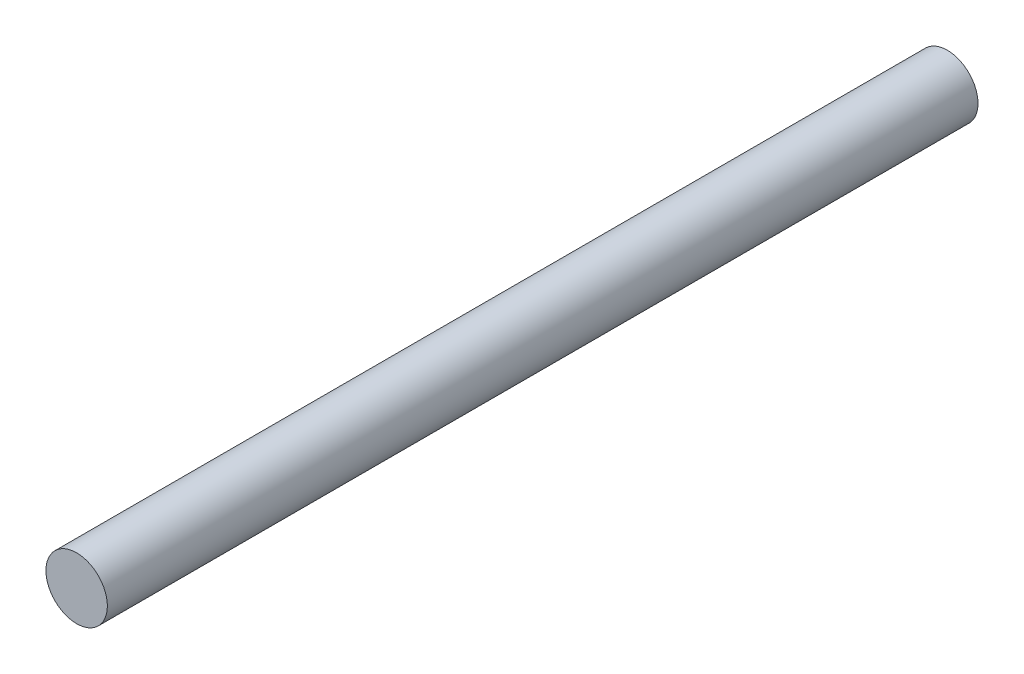
SolidWorks part; units mm, degrees
ref_plane "Front" through (0, 0, 0) normal (0, 0, 1) x (1, 0, 0)
ref_plane "Top" through (0, 0, 0) normal (0, 1, 0) x (1, 0, 0)
ref_plane "Right" through (0, 0, 0) normal (1, 0, 0) x (0, 0, -1)
sketch "Sketch1" plane through (0, 0, 0) normal (0, 0, 1) x (1, 0, 0)
  circle A0 centre (0, 0) radius 14.64
  dimension "D1" = 29.28
extrude "Extrude1" add sketch "Sketch1" along normal blind 415
sketch "Sketch2" plane through (0, 0, 0) normal (0, 1, 0) x (1, 0, 0)
  line L0 (0, 0) -> (0, -415) construction
  line L1 (14.64, 0) -> (-14.64, 0) construction
  line L2 (-14.64, -415) -> (14.64, -415) construction
